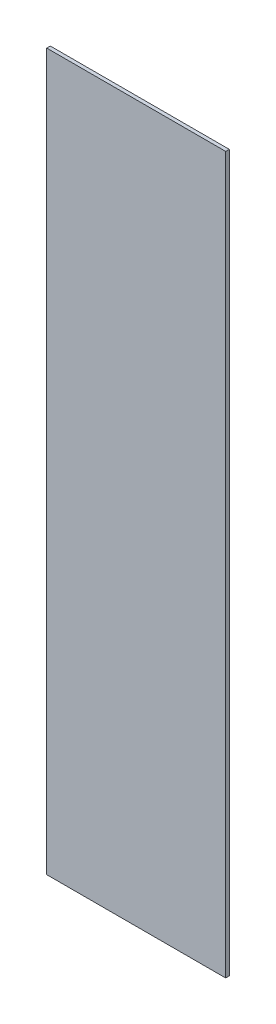
SolidWorks part; units mm, degrees
material "Copper"
ref_plane "Front Plane" through (0, 0, 0) normal (0, 0, 1) x (1, 0, 0)
ref_plane "Top Plane" through (0, 0, 0) normal (0, 1, 0) x (1, 0, 0)
ref_plane "Right Plane" through (0, 0, 0) normal (1, 0, 0) x (0, 0, -1)
sketch "BaseSketch" plane through (0, 0, 0) normal (0, 0, 1) x (1, 0, 0)
  line L1 (-635, -2540) -> (635, -2540)
  line L2 (-635, -2540) -> (-635, 2540)
  line L3 (-635, 2540) -> (635, 2540)
  line L4 (635, -2540) -> (635, 2540)
  line L5 (-635, -2540) -> (635, 2540) construction
  line L6 (-635, 2540) -> (635, -2540) construction
  point P0 (0, 0)
  dimension "LENGTH" = 1270
  dimension "WIDTH" = 5080
extrude "BLOCK" add sketch "BaseSketch" along normal blind 25.4
